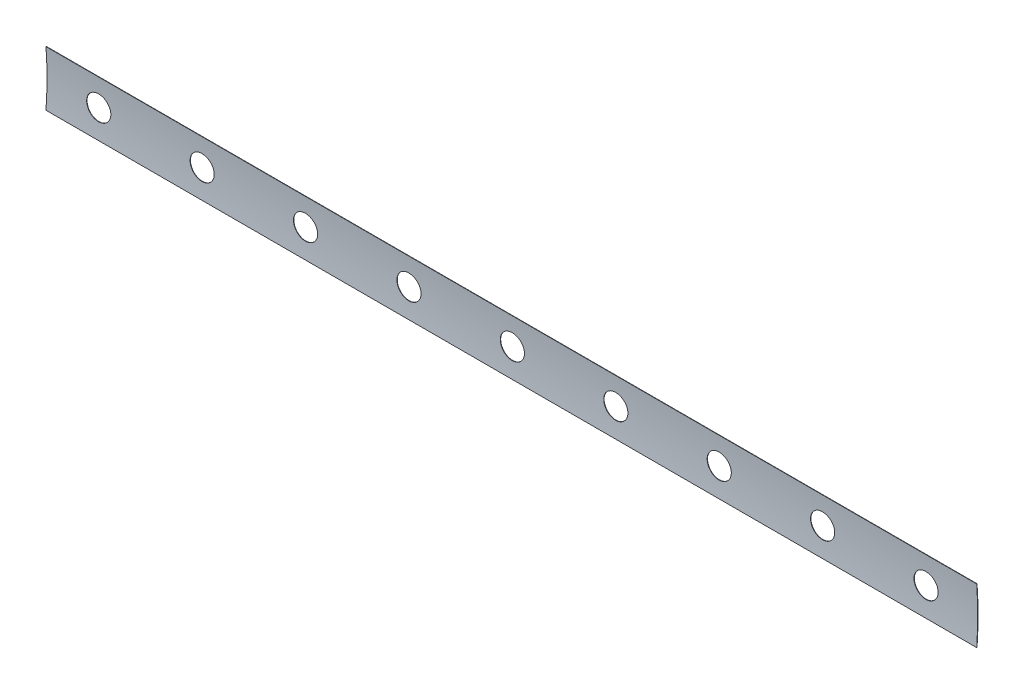
SolidWorks part; units mm, degrees
ref_plane "Front Plane" through (0, 0, 0) normal (0, 0, 1) x (1, 0, 0)
ref_plane "Top Plane" through (0, 0, 0) normal (0, 1, 0) x (1, 0, 0)
ref_plane "Right Plane" through (0, 0, 0) normal (1, 0, 0) x (0, 0, -1)
sketch "Sketch1" plane through (0, 0, 0) normal (1, 0, 0) x (0, 0, -1)
  line L1 (-44.1415, 32.1981) -> (-44.64, 32.16)
  line L2 (-44.64, -47.84) -> (-44.1415, -47.8781)
  arc A0 (-44.64, -47.84) -> (-44.64, 32.16) centre (-568.3656, -7.84) ccw
  arc A1 (-44.1415, -47.8781) -> (-44.1415, 32.1981) centre (-568.3656, -7.84) ccw
  dimension "D1" = 80
  dimension "D2" = 0.5
extrude "Boss-Extrude1" add sketch "Sketch1" along normal blind 1350
sketch "Sketch2" plane through (0, 0, 0) normal (0, 0, 1) x (1, 0, 0)
  line L0 (0, 32.16) -> (0, -47.84) construction
  circle A0 centre (75, -7.84) radius 17.5
  dimension "D1" = 35
  dimension "D2" = 75
extrude "Cut-Extrude1" cut sketch "Sketch2" against normal through all both and the other way through all
pattern_linear "LPattern1" count 9 spacing 150 along (1, 0, 0) of "Cut-Extrude1"
